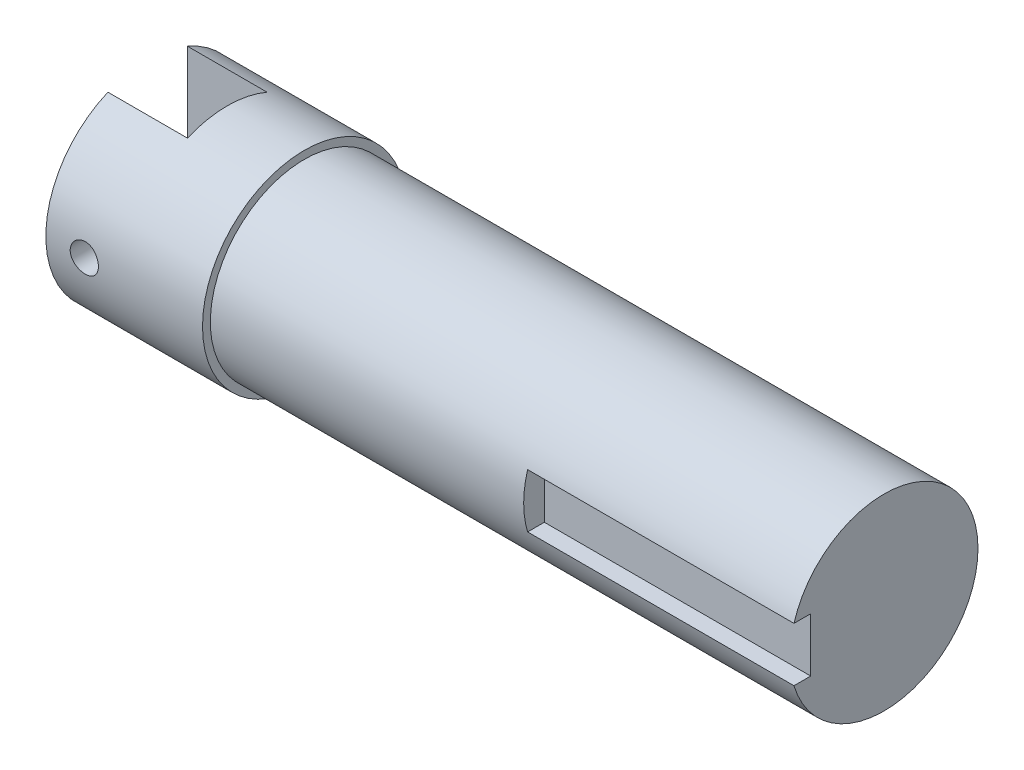
SolidWorks part; units mm, degrees
ref_plane "Front Plane" through (0, 0, 0) normal (1, 0, 0) x (0, 1, 0)
ref_plane "Top Plane" through (0, 0, 0) normal (0, 0, 1) x (0, 1, 0)
ref_plane "Right Plane" through (0, 0, 0) normal (0, 1, 0) x (-1, 0, 0)
sketch "Sketch1" plane through (0, 0, 0) normal (1, 0, 0) x (0, 1, 0)
  circle A0 centre (0, 0) radius 30
  dimension "D1" = 60
extrude "Boss-Extrude1" add sketch "Sketch1" along normal blind 185
sketch "Sketch2" plane through (0, 0, 0) normal (-1, 0, 0) x (0, 0, 1)
  circle A0 centre (0, 0) radius 32.5
  dimension "D1" = 65
extrude "Boss-Extrude2" add sketch "Sketch2" along normal blind 50
sketch "Sketch3" plane through (185, 0, 0) normal (1, 0, 0) x (0, 1, 0)
  line L0 (0, 30) -> (0, 23.4) construction
  line L1 (-8.6135, 34.4) -> (8.6135, 34.4)
  line L2 (-8.6135, 34.4) -> (-8.6135, 23.4)
  line L3 (-8.6135, 23.4) -> (8.6135, 23.4)
  line L4 (8.6135, 34.4) -> (8.6135, 23.4)
  circle A4 centre (0, 0) radius 30 construction
  circle A5 centre (0, 0) radius 30 construction
  point P4 (0, 23.4)
  point P12 (0, 25.2513)
  dimension "D1" = 17.227
  dimension "D3" = 6.6
  dimension "D2" = 11
extrude "Cut-Extrude1" cut sketch "Sketch3" against normal blind 85
sketch "Sketch6" plane through (-50, 0, 0) normal (-1, 0, 0) x (0, -1, 0)
  line L1 (-45.1644, 12.7) -> (51.9653, 12.7)
  line L2 (-45.1644, 12.7) -> (-45.1644, -12.7)
  line L3 (-45.1644, -12.7) -> (51.9653, -12.7)
  line L4 (51.9653, 12.7) -> (51.9653, -12.7)
  point P4 (-45.1644, 0)
  dimension "D1" = 25.4
  dimension "D2" = 45.1644
  dimension "D3" = 0
extrude "Cut-Extrude2" cut sketch "Sketch6" against normal blind 25.4 contours L1 L4 L3 L2
sketch "Sketch7" plane through (0, 0, -12.7) normal (0, 0, 1) x (1, 0, 0)
  circle A0 centre (-37.7298, 0) radius 4.5
  point P2 (0, 0)
  point P3 (-28.3512, 0)
  point P4 (-37.7298, 0)
  point P5 (0, 0)
extrude "Cut-Extrude3" cut sketch "Sketch7" against normal blind 25.4 and the other way blind 66.4
